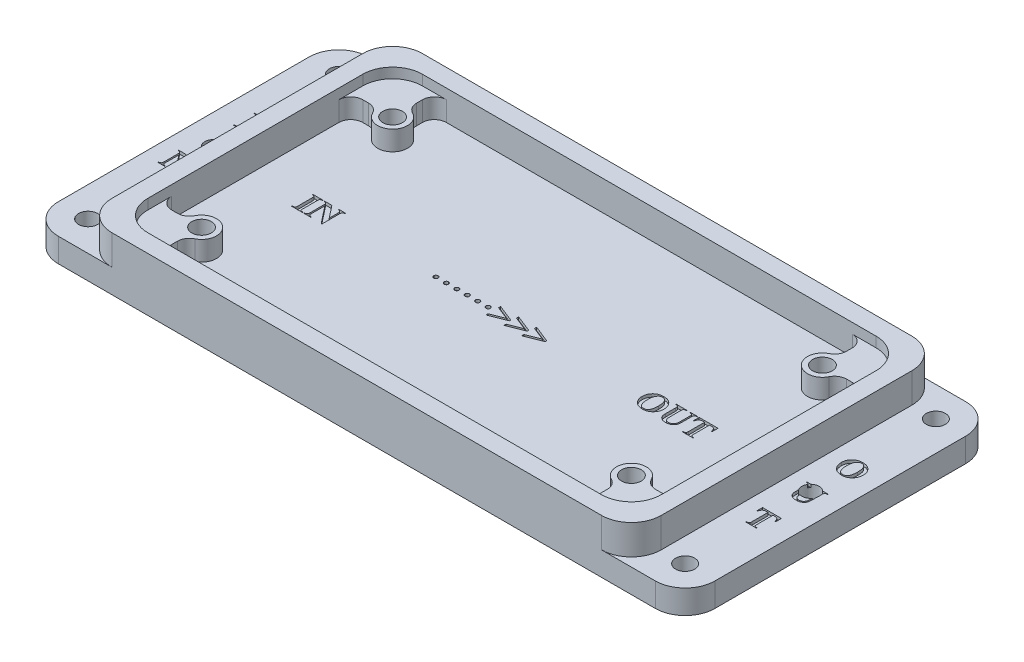
SolidWorks part; units mm, degrees
material "ABS"
ref_plane "前视基准面" through (0, 0, 0) normal (0, 0, 1) x (1, 0, 0)
ref_plane "上视基准面" through (0, 0, 0) normal (0, 1, 0) x (1, 0, 0)
ref_plane "右视基准面" through (0, 0, 0) normal (1, 0, 0) x (0, 0, -1)
other "Configuration Table"
sketch "草图1" plane through (0, 0, 0) normal (0, 1, 0) x (1, 0, 0)
  line L0 (-46, 26) -> (-46, -26)
  line L1 (-43, 23) -> (43, 23)
  line L2 (-43, 23) -> (-43, -23)
  line L3 (-43, -23) -> (43, -23)
  line L4 (43, 23) -> (43, -23)
  line L5 (-43, 23) -> (43, -23) construction
  line L6 (-43, -23) -> (43, 23) construction
  line L7 (-46, -26) -> (46, -26)
  line L8 (46, 26) -> (46, -26)
  line L9 (-46, 26) -> (46, 26)
  point P0 (0, 0)
  dimension "D1" = 46
  dimension "D2" = 86
  dimension "D3" = 3
extrude "凸台-拉伸1" add sketch "草图1" along normal blind 5
sketch "草图2" plane through (0, 0, 0) normal (0, -1, 0) x (1, 0, 0)
  line L0 (-38.5, 16) -> (-43, 16)
  line L1 (-36, 16) -> (36, 16) construction
  line L2 (-36, 16) -> (-36, -16) construction
  line L3 (-36, -16) -> (36, -16) construction
  line L4 (36, 16) -> (36, -16) construction
  line L5 (-36, 16) -> (36, -16) construction
  line L6 (-36, -16) -> (36, 16) construction
  line L7 (-43, -23) -> (-43, 23) construction
  line L8 (-36, 16) -> (-36, 17.65)
  line L9 (-43, 23) -> (43, 23) construction
  line L10 (-38.5, -16) -> (-43, -16)
  line L11 (-36, -18.5) -> (-36, -23)
  line L12 (43, -23) -> (-43, -23) construction
  line L13 (36, -18.5) -> (36, -23)
  line L14 (38.5, -16) -> (43, -16)
  line L15 (43, 23) -> (43, -23) construction
  line L16 (36, 18.5) -> (36, 23)
  line L17 (38.5, 16) -> (43, 16)
  line L18 (43, 23) -> (43, 16)
  line L19 (43, -23) -> (36, -23)
  line L20 (-43, -23) -> (-43, -16)
  line L21 (-43, 23) -> (-36, 23)
  line L22 (36, 23) -> (43, 23)
  line L23 (-43, 16) -> (-43, 23)
  line L24 (-36, -23) -> (-43, -23)
  line L25 (43, -16) -> (43, -23)
  line L26 (-36, 18.5) -> (-36, 23)
  arc A0 (-38.5, 16) -> (-36, 18.5) centre (-36, 16) ccw
  arc A1 (36, 18.5) -> (38.5, 16) centre (36, 16) ccw
  arc A2 (38.5, -16) -> (36, -18.5) centre (36, -16) ccw
  arc A3 (-36, -18.5) -> (-38.5, -16) centre (-36, -16) ccw
  circle A4 centre (-36, -16) radius 1.65
  circle A5 centre (36, -16) radius 1.65
  circle A6 centre (36, 16) radius 1.65
  circle A7 centre (-36, 16) radius 1.65
  point P0 (0, 0)
  line M5 (-43, 23) -> (43, 23)
  line M6 (43, 23) -> (43, -23)
  line M7 (43, -23) -> (-43, -23)
  line M8 (-43, -23) -> (-43, 23)
  dimension "D3" = 5
  dimension "D4" = 3.3
  dimension "D1" = 32
  dimension "D2" = 72
extrude "凸台-拉伸3" add sketch "草图2" against normal up to surface (5 mm away) contours L16 A1 L17 A6 M6 M5 | L14 A2 L13 A5 M7 M6 | L11 A3 L10 A4 M8 M7 | L0 A0 L26 A7 M5 M8 up to face at (0, 5, 0)
fillet "圆角1" radius 2 16 edges at (38.5, 2.5, 16) (43, 2.5, 16) (43, 2.5, -16) (38.5, 2.5, -16) (36, 2.5, -18.5) (36, 2.5, -23) (-36, 2.5, -23) (-36, 2.5, -18.5) (-38.5, 2.5, -16) (-43, 2.5, -16) (-43, 2.5, 16) (-38.5, 2.5, 16) (-36, 2.5, 18.5) (-36, 2.5, 23) (36, 2.5, 23) (36, 2.5, 18.5)
fillet "圆角2" radius 5 4 edges at (-46, 2.5, 26) (46, 2.5, 26) (46, 2.5, -26) (-46, 2.5, -26)
sketch "草图3" plane through (0, 5, 0) normal (0, 1, 0) x (1, 0, 0)
  line L0 (-43, 14) -> (-43, -14) construction
  line L1 (-43, 23) -> (43, 23)
  line L2 (-43, 23) -> (-43, -23)
  line L3 (-43, -23) -> (43, -23)
  line L4 (43, 23) -> (43, -23)
  line L5 (-43, 23) -> (43, -23) construction
  line L6 (-43, -23) -> (43, 23) construction
  line L7 (34, 23) -> (-34, 23) construction
  point P0 (0, 0)
extrude "切除-拉伸1" cut sketch "草图3" against normal blind 1.7
sketch "草图5" plane through (0, 0, 0) normal (0, -1, 0) x (1, 0, 0)
  line L0 (-41, 26) -> (41, 26) construction
  line L1 (-55, 26) -> (55, 26)
  line L2 (-55, 26) -> (-55, -26)
  line L3 (-55, -26) -> (55, -26)
  line L4 (55, 26) -> (55, -26)
  line L5 (-55, 26) -> (55, -26) construction
  line L6 (-55, -26) -> (55, 26) construction
  line L7 (66.4848, 0) -> (-71.1898, 0) construction
  line L8 (-46, -21) -> (-46, 21) construction
  line L9 (-50, 21) -> (50, 21) construction
  line L10 (-50, 21) -> (-50, -21) construction
  line L11 (-50, -21) -> (50, -21) construction
  line L12 (50, 21) -> (50, -21) construction
  line L13 (-50, 21) -> (50, -21) construction
  line L14 (-50, -21) -> (50, 21) construction
  circle A1 centre (-50, 21) radius 1.6
  circle A2 centre (-50, -21) radius 1.6
  circle A3 centre (50, -21) radius 1.6
  circle A4 centre (50, 21) radius 1.6
  circle A5 centre (-50, 0) radius 1.45
  circle A6 centre (50, 0) radius 1.45
  point P0 (0, 0)
  point P8 (0, 0)
  point P25 (51.4512, 0)
  dimension "D2" = 5
  dimension "D5" = 3.2
  dimension "D6" = 2.9
  dimension "D7" = 2.9
  dimension "D1" = 110
  dimension "D3" = 5
  dimension "D4" = 4
extrude "凸台-拉伸4" add sketch "草图5" along normal blind 4
sketch "草图6" plane through (0, -4, 0) normal (0, -1, 0) x (1, 0, 0)
  line L1 (-36, 16) -> (36, 16) construction
  line L2 (-36, 16) -> (-36, -16) construction
  line L3 (-36, -16) -> (36, -16) construction
  line L4 (36, 16) -> (36, -16) construction
  line L5 (-36, 16) -> (36, -16) construction
  line L6 (-36, -16) -> (36, 16) construction
  circle A0 centre (-36, 16) radius 3
  circle A1 centre (-36, -16) radius 3
  circle A2 centre (36, -16) radius 3
  circle A3 centre (36, 16) radius 3
  point P0 (0, 0)
  dimension "D3" = 6
  dimension "D1" = 32
  dimension "D2" = 72
extrude "切除-拉伸2" cut sketch "草图6" against normal blind 3
fillet "圆角3" radius 5 8 edges at (43, 4.15, -23) (43, 4.15, 23) (-43, 4.15, 23) (-43, 4.15, -23) (55, -2, 26) (55, -2, -26) (-55, -2, -26) (-55, -2, 26)
sketch "草图7" plane through (0, 0, 0) normal (0, 1, 0) x (1, 0, 0)
  text T0 "<b>I</b>" font "Times New Roman" height 3.5
  text T1 "<b>N</b>" font "Times New Roman" height 3.5
  text T2 "<b>O</b>\r\n<b>U</b>\r\n<b>T</b>"
  text T3 "<b>IN            ······>>>            OUT</b>\r\n"
extrude "切除-拉伸3" cut sketch "草图7" against normal blind 0.5
sketch "草图8" plane through (0, 0, 0) normal (0, 1, 0) x (1, 0, 0)
  circle A0 centre (-36, -16) radius 1.65
  circle A1 centre (-36, 16) radius 1.65
  circle A2 centre (36, 16) radius 1.65
  circle A3 centre (36, -16) radius 1.65
  circle A4 centre (-36, -16) radius 1.65 construction
  circle A7 centre (36, -16) radius 1.65 construction
  circle A8 centre (36, 16) radius 1.65 construction
  circle A9 centre (-36, 16) radius 1.65 construction
extrude "切除-拉伸4" cut sketch "草图8" against normal through all
